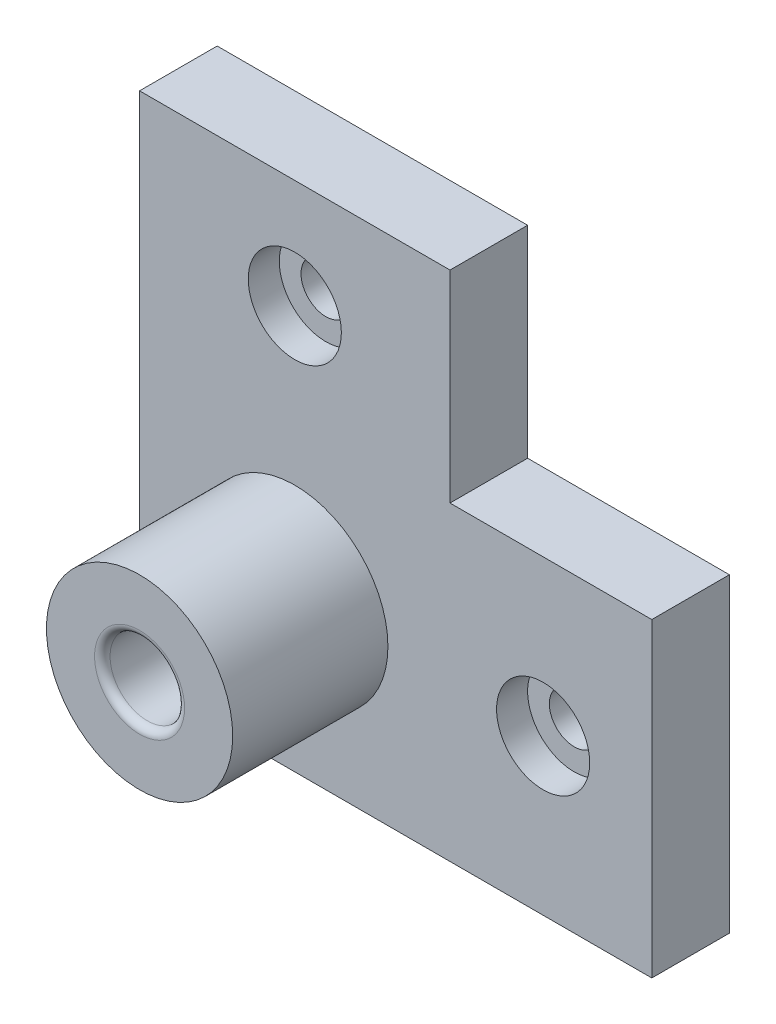
SolidWorks part; units mm, degrees
ref_plane "前视基准面" through (0, 0, 0) normal (0, 0, 1) x (1, 0, 0)
ref_plane "上视基准面" through (0, 0, 0) normal (0, 1, 0) x (1, 0, 0)
ref_plane "右视基准面" through (0, 0, 0) normal (1, 0, 0) x (0, 0, -1)
sketch "草图1" plane through (0, 0, 0) normal (0, 0, 1) x (1, 0, 0)
  line L0 (10, 0) -> (10, 50000) construction
  line L1 (0, 0) -> (20, 0)
  line L2 (0, 0) -> (0, 33)
  line L3 (0, 33) -> (20, 33)
  line L4 (20, 0) -> (20, 33)
  line L5 (0, 0) -> (33, 0)
  line L6 (0, 0) -> (0, 20)
  line L7 (0, 20) -> (33, 20)
  line L8 (33, 0) -> (33, 20)
  line L9 (50.837, 10) -> (-49949.163, 10) construction
  circle A0 centre (10, 26) radius 1.6
  circle A1 centre (26, 10) radius 1.6
  point P10 (10, 0)
  point P13 (33, 10)
  dimension "D3" = 3.2
  dimension "D4" = 3.2
  dimension "D1" = 20
  dimension "D2" = 20
  dimension "D5" = 16
  dimension "D6" = 16
  dimension "D7" = 23
  dimension "D8" = 23
extrude "凸台-拉伸1" add sketch "草图1" along normal blind 5 contours L7 L2 L1 L4 | L2 L7 L4 L3 A0 | L5 L8 L7 L4 A1
sketch "草图2" plane through (0, 0, 5) normal (0, 0, 1) x (1, 0, 0)
  line L0 (10, 33) -> (10, 9.112) construction
  line L1 (0, 33) -> (20, 33) construction
  line L2 (33, 10) -> (-49967, 10) construction
  line L3 (33, 0) -> (33, 20) construction
  circle A0 centre (10, 10) radius 6
  point P8 (33, 10)
  dimension "D1" = 12
extrude "凸台-拉伸2" add sketch "草图2" along normal blind 10
sketch "草图3" plane through (0, 0, 15) normal (0, 0, 1) x (1, 0, 0)
  circle A0 centre (10, 10) radius 2.4
  dimension "D1" = 4.8
extrude "切除-拉伸1" cut sketch "草图3" against normal through all
sketch "草图4" plane through (0, 0, 5) normal (0, 0, 1) x (1, 0, 0)
  circle A0 centre (10, 26) radius 3
  circle A1 centre (26, 10) radius 3
  dimension "D1" = 6
  dimension "D2" = 6
extrude "切除-拉伸2" cut sketch "草图4" against normal blind 2
fillet "圆角1" radius 0.5 1 edges at (12.4, 10, 15)
